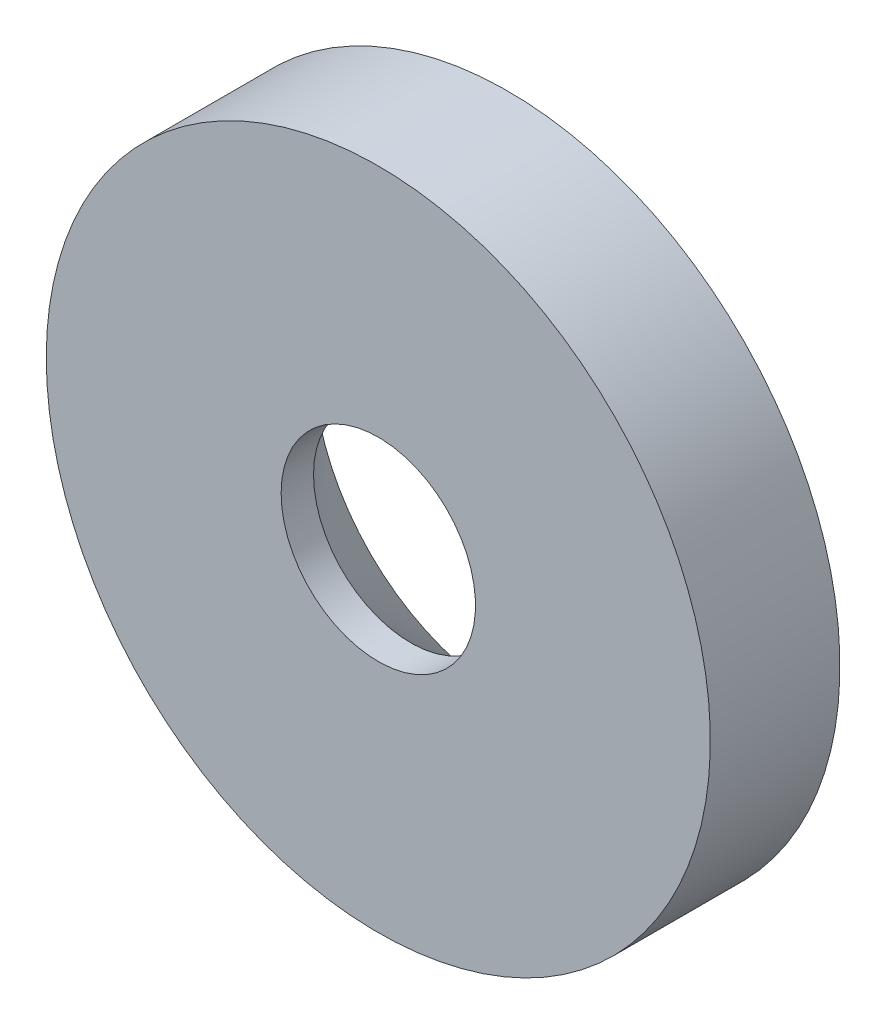
SolidWorks part; units mm, degrees
ref_plane "Front Plane" through (0, 0, 0) normal (0, 0, 1) x (1, 0, 0)
ref_plane "Top Plane" through (0, 0, 0) normal (0, 1, 0) x (1, 0, 0)
ref_plane "Right Plane" through (0, 0, 0) normal (1, 0, 0) x (0, 0, -1)
sketch "Sketch1" plane through (0, 0, 0) normal (0, 1, 0) x (1, 0, 0)
  line L0 (6, 0) -> (20.5, 0)
  line L1 (20.5, 0) -> (20.5, 8)
  line L2 (20.5, 8) -> (12, 8)
  line L4 (0, 17.2571) -> (0, -8) construction
  line L5 (6, 2) -> (12, 8)
  line L7 (6, 2) -> (6, 0)
  dimension "D1" = 8
  dimension "D2" = 12
  dimension "D3" = 2
  dimension "D4" = 45
  dimension "D5" = 41
revolve "Revolve1" add sketch "Sketch1" angle 360 about L4
